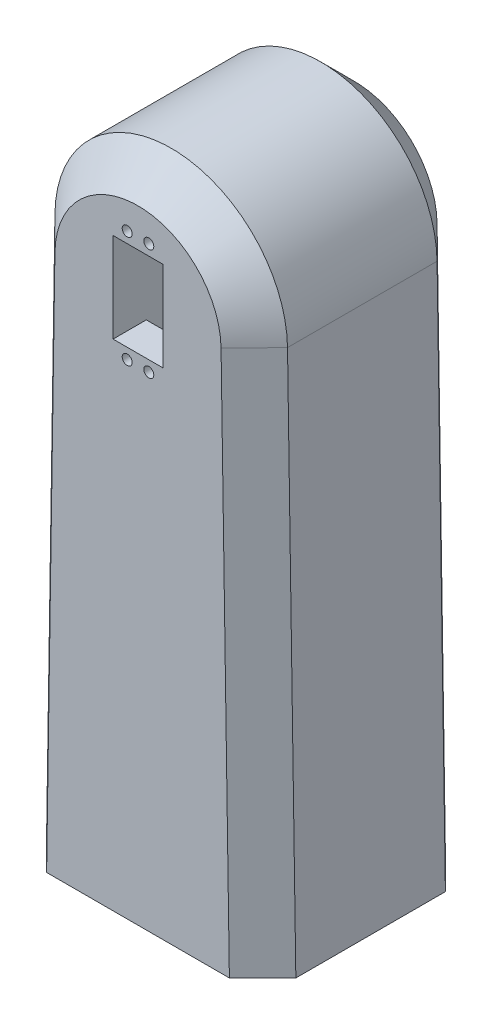
SolidWorks part; units mm, degrees
ref_plane "Front Plane" through (0, 0, 0) normal (0, 0, 1) x (1, 0, 0)
ref_plane "Top Plane" through (0, 0, 0) normal (0, 1, 0) x (1, 0, 0)
ref_plane "Right Plane" through (0, 0, 0) normal (1, 0, 0) x (0, 0, -1)
sketch "Sketch1" plane through (0, 0, 0) normal (0, 0, 1) x (1, 0, 0)
  line L0 (-37.5, 0) -> (37.5, 0)
  line L1 (0, -1000) -> (0, 49000) construction
  line L2 (37.5, 0) -> (34.9959, 163.0375)
  line L3 (-37.5, 0) -> (-34.9959, 163.0375)
  arc A0 (34.9959, 163.0375) -> (-34.9959, 163.0375) centre (0, 162.5) ccw
  point P4 (0, 0)
  dimension "D2" = 70
  dimension "D1" = 75
  dimension "D3" = 162.5
extrude "Boss-Extrude1" add sketch "Sketch1" along normal blind 65
chamfer "Chamfer1" distance 10 6 edges at (-36.2479, 81.5188, 0) (0, 197.5, 0) (36.2479, 81.5188, 0) (-36.2479, 81.5188, 65) (36.2479, 81.5188, 65) (0, 197.5, 65)
sketch "Sketch2" plane through (0, 0, 0) normal (0, -1, 0) x (-1, 0, 0)
  line L0 (0, -65) -> (0, 0) construction
  line L1 (27.4988, -65) -> (-27.4988, -65) construction
  circle A0 centre (0, -32.5) radius 15
  dimension "D1" = 30
extrude "Cut-Extrude1" cut sketch "Sketch2" against normal blind 5
sketch "Sketch3" plane through (0, 5, 0) normal (0, -1, 0) x (-1, 0, 0)
  line L0 (0, -47.5) -> (0, -17.5) construction
  line L1 (15, -32.5) -> (-15, -32.5) construction
  circle A0 centre (0, -32.5) radius 15 construction
  circle A1 centre (0, -32.5) radius 15 construction
  circle A2 centre (0, -40) radius 1.5
  circle A3 centre (-7.5, -32.5) radius 1.5
  circle A4 centre (0, -25) radius 1.5
  circle A5 centre (7.5, -32.5) radius 1.5
  point P13 (0, -32.5)
  point P21 (0, -32.5)
  dimension "D1" = 3
  dimension "D2" = 7.5
  dimension "D3" = 4
extrude "Cut-Extrude2" cut sketch "Sketch3" against normal blind 7.5
fillet "Fillet1" radius 1 2 edges at (0, 0, 17.5) (0, 5, 17.5)
sketch "Sketch4" plane through (0, 0, 0) normal (0, 0, -1) x (-1, 0, 0)
  line L1 (-7.5, 182.5) -> (7.5, 182.5)
  line L2 (-7.5, 182.5) -> (-7.5, 142.5)
  line L3 (-7.5, 142.5) -> (7.5, 142.5)
  line L4 (7.5, 182.5) -> (7.5, 142.5)
  line L5 (-7.5, 182.5) -> (7.5, 142.5) construction
  line L6 (-7.5, 142.5) -> (7.5, 182.5) construction
  point P0 (0, 162.5)
  dimension "D1" = 40
  dimension "D2" = 15
extrude "Cut-Extrude3" cut sketch "Sketch4" against normal offset from surface (55 mm away) 10 up to face at (0, 87.596, 65)
sketch "Sketch5" plane through (0, 0, 55) normal (0, 0, -1) x (-1, 0, 0)
  line L0 (7.5, 142.5) -> (7.5, 182.5) construction
  line L1 (-7.5, 182.5) -> (7.5, 182.5)
  line L2 (-7.5, 182.5) -> (-7.5, 176)
  line L3 (-7.5, 176) -> (7.5, 176)
  line L4 (7.5, 182.5) -> (7.5, 176)
  line L5 (-7.5, 182.5) -> (-7.5, 142.5) construction
  line L6 (7.5, 142.5) -> (-7.5, 142.5)
  line L7 (7.5, 142.5) -> (7.5, 149)
  line L8 (7.5, 149) -> (-7.5, 149)
  line L9 (-7.5, 142.5) -> (-7.5, 149)
  line L10 (-7.5, 176) -> (-7.5, 149)
  line L11 (7.5, 176) -> (7.5, 149)
  line L12 (0, 182.5) -> (0, 142.5) construction
  line L13 (7.5, 162.5) -> (-7.5, 162.5) construction
  circle A0 centre (-3.25, 179.25) radius 1.5
  circle A1 centre (3.25, 179.25) radius 1.5
  circle A2 centre (3.25, 145.75) radius 1.5
  circle A3 centre (-3.25, 145.75) radius 1.5
  line M13 (7.5, 142.5) -> (7.5, 182.5)
  line M15 (-7.5, 182.5) -> (-7.5, 142.5)
  dimension "D3" = 3
  dimension "D1" = 6.5
  dimension "D2" = 6.5
  dimension "D4" = 3.25
  dimension "D5" = 3.25
extrude "Cut-Extrude4" cut sketch "Sketch5" against normal through all contours L8 L3 M13 M15 | A0 | A1 | A3 | A2
sketch "Sketch6" plane through (0, 0, 65) normal (0, 0, 1) x (1, 0, 0)
  line L0 (0, 176) -> (0, 149) construction
  line L1 (7.5, 176) -> (-7.5, 176) construction
  line L2 (-7.5, 149) -> (7.5, 149) construction
  circle A0 centre (0, 162.5) radius 3.75 construction
  dimension "D1" = 7.5
